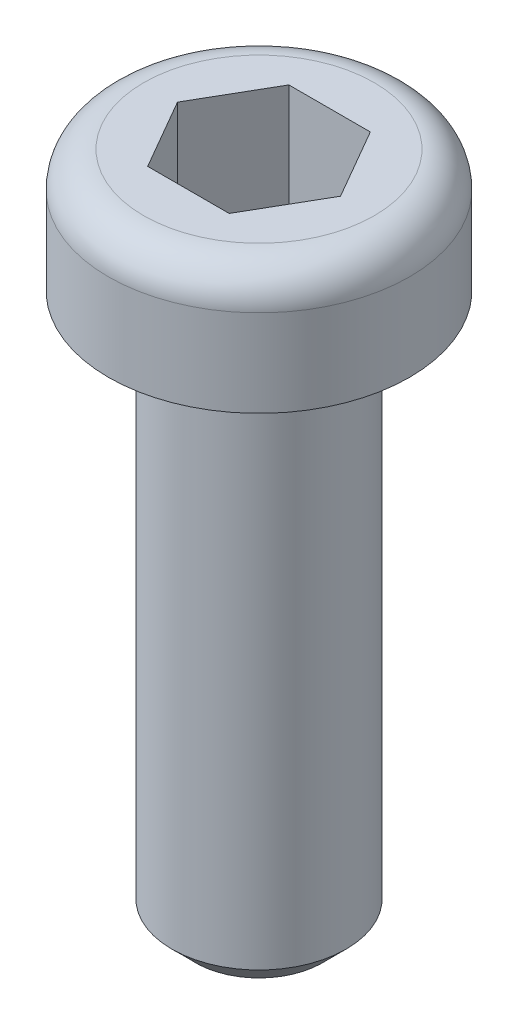
SolidWorks part; units mm, degrees
ref_plane "Front Plane" through (0, 0, 0) normal (0, 0, 1) x (1, 0, 0)
ref_plane "Top Plane" through (0, 0, 0) normal (0, 1, 0) x (1, 0, 0)
ref_plane "Right Plane" through (0, 0, 0) normal (1, 0, 0) x (0, 0, -1)
sketch "Sketch1" plane through (0, 0, 0) normal (0, 1, 0) x (1, 0, 0)
  line L1 (1.7321, 0) -> (0.866, 1.5)
  line L2 (0.866, 1.5) -> (-0.866, 1.5)
  line L3 (-0.866, 1.5) -> (-1.7321, 0)
  line L4 (-1.7321, 0) -> (-0.866, -1.5)
  line L5 (-0.866, -1.5) -> (0.866, -1.5)
  line L6 (0.866, -1.5) -> (1.7321, 0)
  circle A0 centre (0, 0) radius 3.2
  circle A1 centre (0, 0) radius 1.5 construction
  dimension "D1" = 6.4
  dimension "D2" = 3
extrude "Boss-Extrude1" add sketch "Sketch1" along normal blind 2.6
fillet "Fillet1" radius 0.75 1 edges at (0, 2.6, 3.2)
sketch "Sketch2" plane through (0, 0, 0) normal (0, -1, 0) x (1, 0, 0)
  circle A0 centre (0, 0) radius 1.85
  dimension "D1" = 3.7
extrude "Boss-Extrude2" add sketch "Sketch2" along normal blind 11.7
chamfer "Chamfer1" distance 0.5 angle 45 1 edges at (0, -11.7, -1.85)
